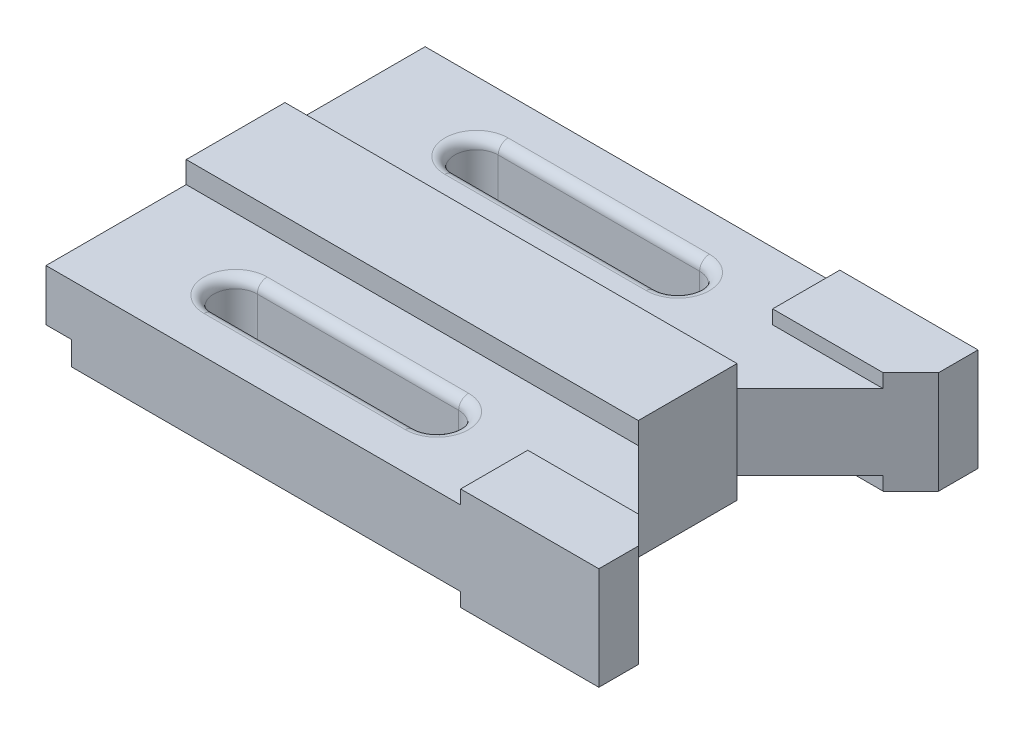
SolidWorks part; units mm, degrees
material "1060 Alloy"
ref_plane "Front Plane" through (0, 0, 0) normal (0, 0, 1) x (1, 0, 0)
ref_plane "Top Plane" through (0, 0, 0) normal (0, 1, 0) x (1, 0, 0)
ref_plane "Right Plane" through (0, 0, 0) normal (1, 0, 0) x (0, 0, -1)
sketch "Sketch1" plane through (0, 0, 0) normal (0, 1, 0) x (1, 0, 0)
  line L0 (0, 0) -> (140, 0)
  line L1 (0, 0) -> (0, 35.5)
  line L2 (0, 35.5) -> (114.5, 35.5)
  line L3 (114.5, 35.5) -> (140, 10)
  line L4 (140, 10) -> (140, 0)
  line L5 (0, 0) -> (0, 185.4521) construction
  line L6 (104.1936, 0) -> (104.1936, 17) construction
  line L7 (104.1936, 17) -> (133, 17) construction
  dimension "D1" = 140
  dimension "D2" = 10
  dimension "D3" = 35.5
  dimension "D4" = 17
  dimension "D5" = 45
extrude "Boss-Extrude1" add sketch "Sketch1" along normal blind 19
sketch "Sketch2" plane through (0, 19, 0) normal (0, 1, 0) x (1, 0, 0)
  line L1 (140, 0) -> (105, 0)
  line L2 (140, 0) -> (140, 10)
  line L3 (133, 17) -> (105, 17)
  line L4 (105, 0) -> (105, 17)
  line L5 (140, 10) -> (133, 17)
  line L6 (140, 10) -> (114.5, 35.5) construction
  dimension "D2" = 35
extrude "Boss-Extrude2" add sketch "Sketch2" along normal blind 3.5
sketch "Sketch3" plane through (0, 0, 0) normal (0, -1, 0) x (1, 0, 0)
  line L0 (140, -10) -> (133, -17)
  line L1 (140, 0) -> (105, 0)
  line L2 (140, 0) -> (140, -10)
  line L3 (133, -17) -> (105, -17)
  line L4 (105, 0) -> (105, -17)
  dimension "D1" = 35
extrude "Boss-Extrude3" add sketch "Sketch3" along normal blind 3.5
sketch "Sketch4" plane through (0, 0, -35.5) normal (0, 0, -1) x (-1, 0, 0)
  line L0 (-57.25, 19) -> (-57.25, 0) construction
  line L1 (-114.5, 19) -> (0, 19) construction
  line L2 (-114.5, 0) -> (0, 0) construction
  line L3 (-114.5, 9.5) -> (0, 9.5) construction
  line L4 (-114.5, 19) -> (-114.5, 0) construction
  line L5 (0, 19) -> (0, 0) construction
  line L7 (-114.4897, -5.5) -> (-0.0103, -5.5)
  line L8 (-114.4897, -5.5) -> (-114.4897, 24.5)
  line L9 (-114.4897, 24.5) -> (-0.0103, 24.5)
  line L10 (-0.0103, -5.5) -> (-0.0103, 24.5)
  line L11 (-114.4897, -5.5) -> (-0.0103, 24.5) construction
  line L12 (-114.4897, 24.5) -> (-0.0103, -5.5) construction
  point P12 (-57.25, 9.5)
  dimension "D1" = 5.5
  dimension "D2" = 30
extrude "Boss-Extrude4" add sketch "Sketch4" along normal blind 25
sketch "Sketch5" plane through (0, 19, 0) normal (0, 1, 0) x (1, 0, 0)
  line L0 (30.5, 17.5) -> (81.5, 17.5) construction
  line L1 (30.5, 23) -> (81.5, 23)
  line L2 (30.5, 12) -> (81.5, 12)
  line L3 (0, 35.5) -> (0, 0) construction
  line L4 (0, 0) -> (105, 0) construction
  arc A0 (30.5, 23) -> (30.5, 12) centre (30.5, 17.5) ccw
  arc A1 (81.5, 12) -> (81.5, 23) centre (81.5, 17.5) ccw
  point P2 (56, 17.5)
  dimension "D4" = 5.5
  dimension "D1" = 30.5
  dimension "D2" = 17.5
  dimension "D3" = 51
extrude "Cut-Extrude1" cut sketch "Sketch5" against normal blind 25
fillet "Fillet1" radius 2.5 8 edges at (87, 19, -17.5) (87, 0, -17.5) (56, 0, -23) (25, 0, -17.5) (56, 19, -23) (25, 19, -17.5) (56, 0, -12) (56, 19, -12)
sketch "Sketch7" plane through (0, 0, 0) normal (0, 1, 0) x (1, 0, 0)
  line L0 (0.0103, 60.5) -> (0.0103, 96)
  line L4 (114.5103, 60.5) -> (0.0103, 60.5)
  line L5 (140.0103, 96) -> (0.0103, 96)
  line L6 (114.5103, 60.5) -> (105.0103, 60.5) construction
  line L10 (114.5103, 60.5) -> (140.0103, 86)
  line L11 (140.0103, 86) -> (140.0103, 96)
  line L18 (140.0103, 96) -> (105.0103, 96) construction
  line L19 (140.0103, 96) -> (140.0103, 79) construction
  line L20 (140.0103, 79) -> (105.0103, 79) construction
  line L21 (105.0103, 96) -> (105.0103, 79) construction
  dimension "D1" = 17
  dimension "D2" = 35
  dimension "D3" = 140
  dimension "D4" = 45
  dimension "D5" = 10
  dimension "D6" = 35.5
extrude "Boss-Extrude8" add sketch "Sketch7" along normal blind 19
sketch "Sketch10" plane through (0, 19, 0) normal (0, 1, 0) x (1, 0, 0)
  line L0 (140.0103, 86) -> (133.0103, 79)
  line L1 (140.0103, 96) -> (105.0103, 96)
  line L2 (140.0103, 96) -> (140.0103, 86)
  line L3 (133.0103, 79) -> (105.0103, 79)
  line L4 (105.0103, 96) -> (105.0103, 79)
  line L5 (114.5103, 60.5) -> (140.0103, 86) construction
  dimension "D1" = 17
  dimension "D2" = 35
extrude "Boss-Extrude9" add sketch "Sketch10" along normal blind 3.5
sketch "Sketch11" plane through (0, 0, 0) normal (0, -1, 0) x (1, 0, 0)
  line L0 (133.0103, -79) -> (140.0103, -86)
  line L1 (140.0103, -96) -> (105.0103, -96)
  line L2 (140.0103, -96) -> (140.0103, -86)
  line L3 (133.0103, -79) -> (105.0103, -79)
  line L4 (105.0103, -96) -> (105.0103, -79)
  dimension "D1" = 28
extrude "Boss-Extrude10" add sketch "Sketch11" along normal blind 3.5
sketch "Sketch12" plane through (0, 0, 0) normal (0, -1, 0) x (1, 0, 0)
  line L0 (30.5103, -78.5) -> (81.5103, -78.5) construction
  line L1 (30.5103, -73) -> (81.5103, -73)
  line L2 (30.5103, -84) -> (81.5103, -84)
  line L3 (0.0103, -96) -> (0.0103, -60.5) construction
  line L4 (105.0103, -96) -> (0.0103, -96) construction
  arc A0 (30.5103, -73) -> (30.5103, -84) centre (30.5103, -78.5) ccw
  arc A1 (81.5103, -84) -> (81.5103, -73) centre (81.5103, -78.5) ccw
  point P2 (56.0103, -78.5)
  dimension "D4" = 5.5
  dimension "D1" = 30.5
  dimension "D2" = 17.5
  dimension "D3" = 51
extrude "Cut-Extrude2" cut sketch "Sketch12" against normal blind 43.5
fillet "Fillet2" radius 2.5 8 edges at (25.0103, 19, -78.5) (56.0103, 19, -84) (87.0103, 19, -78.5) (56.0103, 19, -73) (56.0103, 0, -73) (25.0103, 0, -78.5) (87.0103, 0, -78.5) (56.0103, 0, -84)
sketch "Sketch13" plane through (0, 0, 0) normal (0, 0, 1) x (1, 0, 0)
  line L1 (0.0103, -5.5) -> (6.5103, -5.5)
  line L2 (0.0103, -5.5) -> (0.0103, 6)
  line L3 (0.0103, 6) -> (6.5103, 6)
  line L4 (6.5103, -5.5) -> (6.5103, 6)
  dimension "D1" = 11.5
  dimension "D2" = 6.5
extrude "Cut-Extrude4" cut sketch "Sketch13" against normal through all
sketch "Sketch14" plane through (0, 0, 0) normal (-1, 0, 0) x (0, 0, 1)
  line L1 (-35.5, 6) -> (0, 6)
  line L2 (-35.5, 6) -> (-35.5, 0)
  line L3 (-35.5, 0) -> (0, 0)
  line L4 (0, 6) -> (0, 0)
extrude "Cut-Extrude5" cut sketch "Sketch14" against normal blind 1.5
equation "\"A\"= 140mm"
equation "\"B\"= 51mm"
equation "\"C\"= 45deg"
